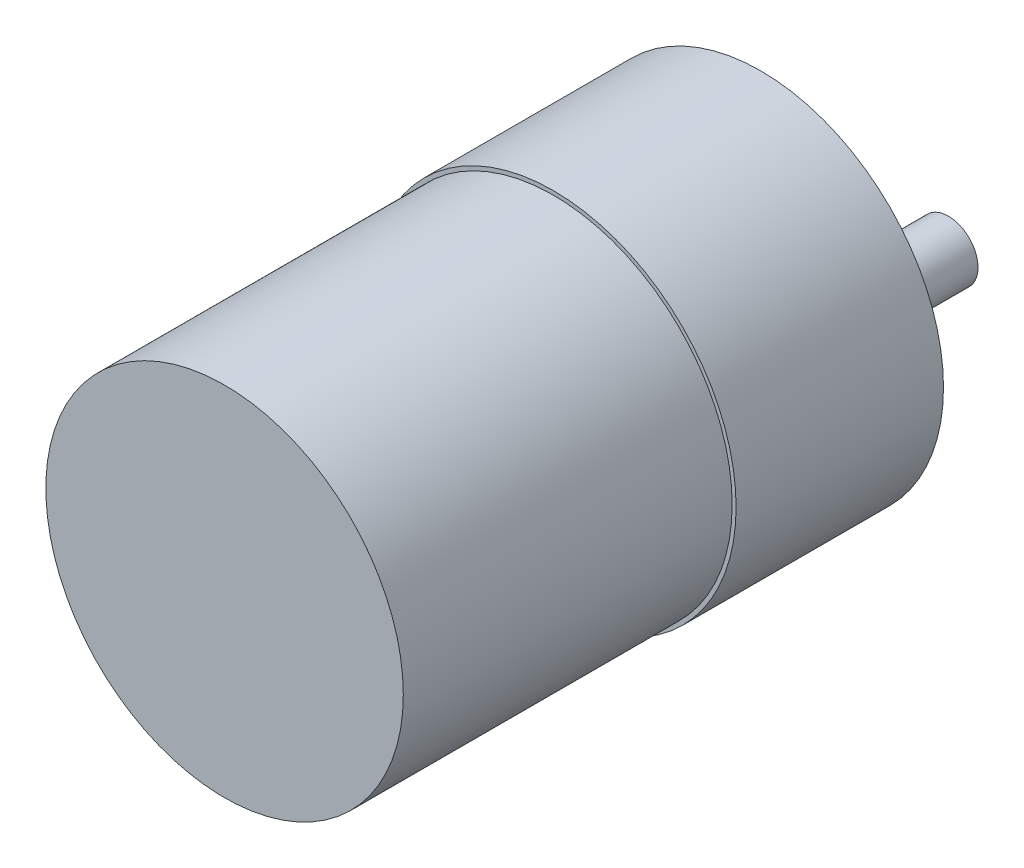
SolidWorks part; units mm, degrees
ref_plane "Front Plane" through (0, 0, 0) normal (0, 0, 1) x (1, 0, 0)
ref_plane "Top Plane" through (0, 0, 0) normal (0, 1, 0) x (1, 0, 0)
ref_plane "Right Plane" through (0, 0, 0) normal (1, 0, 0) x (0, 0, -1)
sketch "Sketch1" plane through (0, 0, 0) normal (0, 0, 1) x (1, 0, 0)
  circle A0 centre (0, 0) radius 18.5
  dimension "D1" = 37
extrude "Inner" add sketch "Sketch1" along normal blind 21
sketch "Sketch2" plane through (0, 0, 21) normal (0, 0, 1) x (1, 0, 0)
  circle A0 centre (0, 0) radius 18.1
  dimension "D1" = 36.2
extrude "Outer" add sketch "Sketch2" along normal blind 33.3
sketch "Sketch3" plane through (0, 0, 0) normal (0, 0, -1) x (-1, 0, 0)
  line L0 (0, -12.742) -> (0, 18.5) construction
  line L1 (0, -12.742) -> (-6.6873, -12.742) construction
  line L2 (-6.6873, -12.742) -> (-6.6873, -0.742) construction
  circle A0 centre (0, -6.742) radius 6
  circle A1 centre (0, 0) radius 18.5 construction
  dimension "D1" = 31.242
  dimension "D2" = 12
extrude "Boss-Extrude3" add sketch "Sketch3" along normal blind 5
sketch "Sketch7" plane through (0, 0, -5) normal (0, 0, -1) x (-1, 0, 0)
  circle A0 centre (0, -6.742) radius 3
  dimension "D1" = 6
extrude "Boss-Extrude6" add sketch "Sketch7" along normal blind 14
